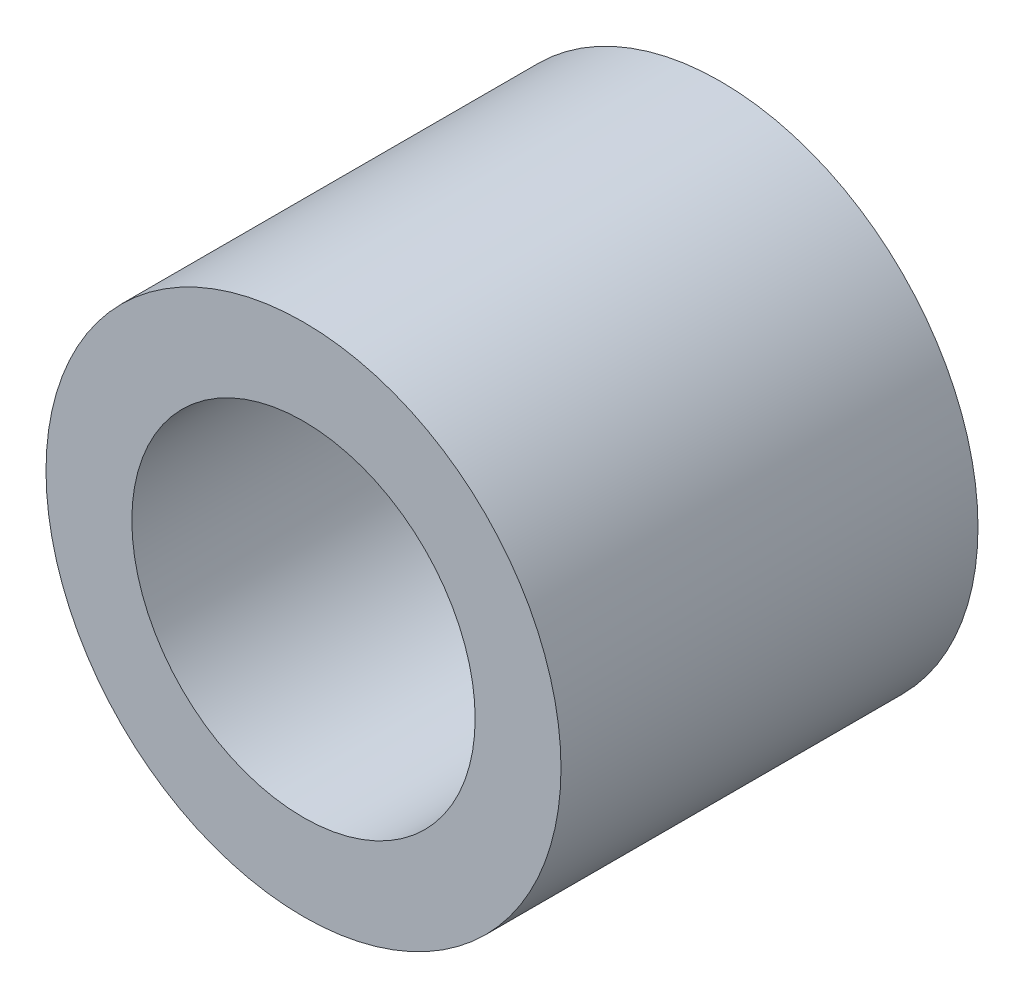
SolidWorks part; units mm, degrees
material "PET"
ref_plane "Front Plane" through (0, 0, 0) normal (0, 0, 1) x (1, 0, 0)
ref_plane "Top Plane" through (0, 0, 0) normal (0, 1, 0) x (1, 0, 0)
ref_plane "Right Plane" through (0, 0, 0) normal (1, 0, 0) x (0, 0, -1)
sketch "Sketch1" plane through (0, 0, 0) normal (0, 0, 1) x (1, 0, 0)
  circle A0 centre (0, 0) radius 6.35
  circle A1 centre (0, 0) radius 9.525
  dimension "D1" = 12.7
  dimension "D2" = 19.05
extrude "Boss-Extrude1" add sketch "Sketch1" along normal mid plane 15.4254
